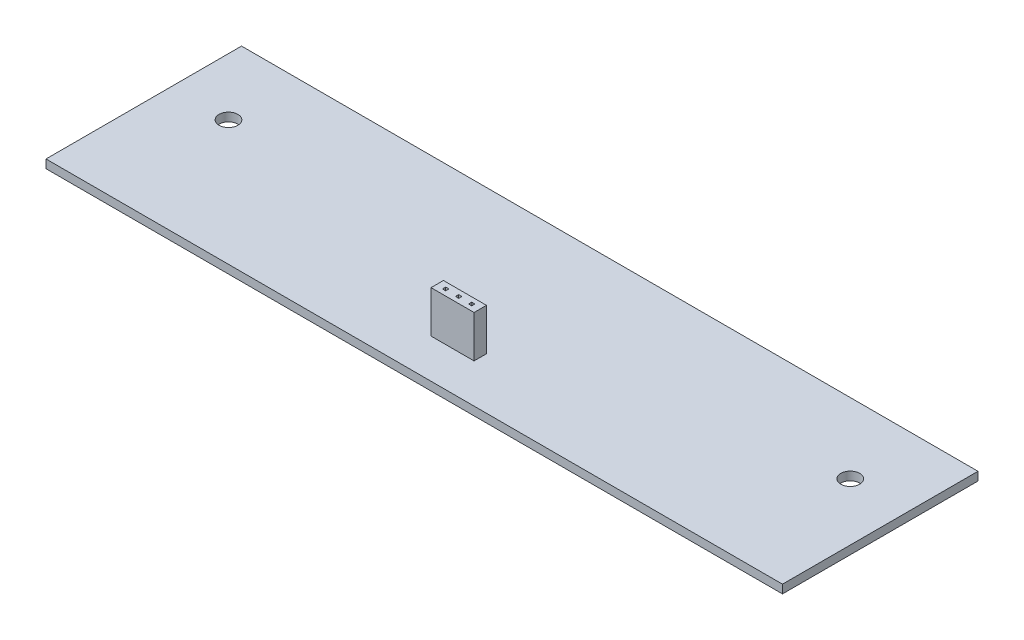
SolidWorks part; units mm, degrees
ref_plane "Plan de face" through (0, 0, 0) normal (0, 0, 1) x (1, 0, 0)
ref_plane "Plan de dessus" through (0, 0, 0) normal (0, 1, 0) x (1, 0, 0)
ref_plane "Plan de droite" through (0, 0, 0) normal (1, 0, 0) x (0, 0, -1)
sketch "Esquisse1" plane through (0, 0, 0) normal (0, 1, 0) x (1, 0, 0)
  line L1 (-71.755, 19.05) -> (71.755, 19.05)
  line L2 (-71.755, 19.05) -> (-71.755, -19.05)
  line L3 (-71.755, -19.05) -> (71.755, -19.05)
  line L4 (71.755, 19.05) -> (71.755, -19.05)
  line L5 (-71.755, 19.05) -> (71.755, -19.05) construction
  line L6 (-71.755, -19.05) -> (71.755, 19.05) construction
  point P0 (0, 0)
  dimension "D1" = 38.1
  dimension "D2" = 143.51
extrude "Boss.-Extru.1" add sketch "Esquisse1" along normal blind 1.651
sketch "Esquisse2" plane through (0, 1.651, 0) normal (0, 1, 0) x (1, 0, 0)
  line L0 (60.579, 19.05) -> (60.579, 5.334) construction
  line L1 (71.755, 19.05) -> (-71.755, 19.05) construction
  line L2 (71.755, 5.334) -> (60.579, 5.334) construction
  line L3 (71.755, -19.05) -> (71.755, 19.05) construction
  line L4 (0, 0) -> (0, 28.8871) construction
  circle A0 centre (60.579, 5.334) radius 1.8415
  circle A1 centre (-60.579, 5.334) radius 1.8415
  dimension "D3" = 3.683
  dimension "D1" = 11.176
  dimension "D2" = 13.716
extrude "Enlèv. mat.-Extru.1" cut sketch "Esquisse2" against normal through all
sketch "Esquisse3" plane through (0, 1.651, 0) normal (0, 1, 0) x (1, 0, 0)
  line L0 (0, -19.05) -> (0, -11.43) construction
  line L1 (-71.755, -19.05) -> (71.755, -19.05) construction
  line L3 (-4.3457, -11.43) -> (-4.3457, -9.017)
  line L4 (-4.3457, -9.017) -> (4.0363, -9.017)
  line L5 (4.0363, -9.017) -> (4.0363, -11.43)
  line L7 (-4.3457, -11.43) -> (4.3457, -11.43)
  point P7 (0, -11.43)
  dimension "D1" = 7.62
  dimension "D2" = 8.382
  dimension "D3" = 2.413
extrude "Boss.-Extru.2" add sketch "Esquisse3" along normal blind 8.1788 contours L3 L7 L5 L4
sketch "Esquisse4" plane through (0, 9.8298, 0) normal (0, 1, 0) x (1, 0, 0)
  line L0 (-0.1547, -9.017) -> (-0.1547, -11.43) construction
  line L1 (-4.3457, -9.017) -> (4.0363, -9.017) construction
  line L2 (-4.3457, -11.43) -> (4.0363, -11.43) construction
  line L3 (-4.3457, -9.017) -> (-0.1547, -9.017) construction
  line L4 (-0.4722, -9.906) -> (0.1628, -9.906)
  line L5 (-0.4722, -9.906) -> (-0.4722, -10.541)
  line L6 (-0.4722, -10.541) -> (0.1628, -10.541)
  line L7 (0.1628, -9.906) -> (0.1628, -10.541)
  line L8 (-0.4722, -9.906) -> (0.1628, -10.541) construction
  line L9 (-0.4722, -10.541) -> (0.1628, -9.906) construction
  line L10 (-0.1547, -9.017) -> (-2.6947, -9.017) construction
  line L11 (-2.6947, -9.017) -> (-2.6947, -11.43) construction
  line L12 (-0.1547, -9.017) -> (2.3853, -9.017) construction
  line L13 (-3.0122, -9.906) -> (-2.3772, -9.906)
  line L14 (-3.0122, -9.906) -> (-3.0122, -10.541)
  line L15 (-3.0122, -10.541) -> (-2.3772, -10.541)
  line L16 (-2.3772, -9.906) -> (-2.3772, -10.541)
  line L17 (-3.0122, -9.906) -> (-2.3772, -10.541) construction
  line L18 (-3.0122, -10.541) -> (-2.3772, -9.906) construction
  line L19 (2.3853, -9.017) -> (2.3853, -11.43) construction
  line L21 (2.0678, -9.906) -> (2.7028, -9.906)
  line L22 (2.0678, -9.906) -> (2.0678, -10.541)
  line L23 (2.0678, -10.541) -> (2.7028, -10.541)
  line L24 (2.7028, -9.906) -> (2.7028, -10.541)
  line L25 (2.0678, -9.906) -> (2.7028, -10.541) construction
  line L26 (2.0678, -10.541) -> (2.7028, -9.906) construction
  point P6 (-0.1547, -10.2235)
  point P12 (-2.6947, -10.2235)
  point P22 (2.3853, -10.2235)
  dimension "D1" = 0.635
  dimension "D2" = 0.635
  dimension "D3" = 2.54
  dimension "D4" = 0.635
  dimension "D5" = 0.635
  dimension "D6" = 2.54
  dimension "D7" = 0.635
  dimension "D8" = 0.635
extrude "Enlèv. mat.-Extru.2" cut sketch "Esquisse4" against normal blind 5.08
